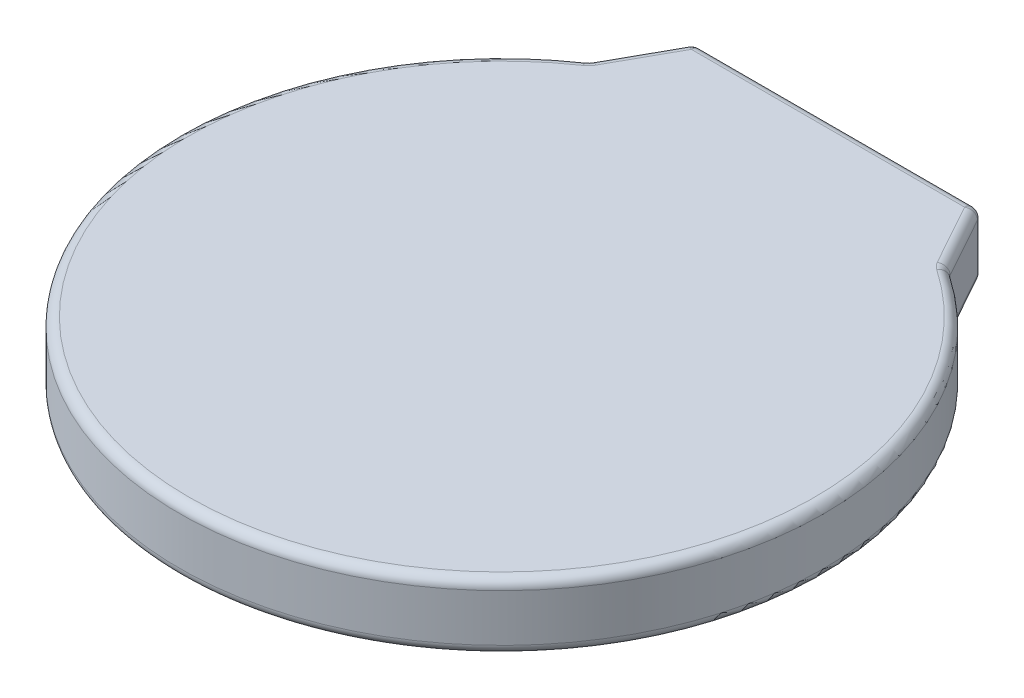
SolidWorks part; units mm, degrees
material "Zinc AC41A Alloy, As Cast"
ref_plane "Front Plane" through (0, 0, 0) normal (0, 0, 1) x (1, 0, 0)
ref_plane "Top Plane" through (0, 0, 0) normal (0, 1, 0) x (1, 0, 0)
ref_plane "Right Plane" through (0, 0, 0) normal (1, 0, 0) x (0, 0, -1)
sketch "Sketch1" plane through (0, 0, 0) normal (0, 1, 0) x (1, 0, 0)
  line L0 (0, -17) -> (0, 17) construction
  line L1 (0, 17) -> (0, 17.7) construction
  line L2 (-7.5, 17.7) -> (7.5, 17.7)
  line L3 (9.5, 14.0979) -> (-9.5, 14.0979) construction
  line L4 (7.5, 17.7) -> (9.5, 14.0979)
  line L5 (-7.5, 17.7) -> (-9.5, 14.0979)
  circle A0 centre (0, 0) radius 17
  point P9 (0, 17.7)
  dimension "D1" = 34
  dimension "D2" = 0.7
  dimension "D3" = 15
  dimension "D4" = 19
extrude "Boss-Extrude1" add sketch "Sketch1" along normal blind 3.5 contours A0 | A0 L4 L2 L5
fillet "Fillet1" radius 0.5 12 edges at (-8.5, 3.5, -15.8989) (-8.5, 0, -15.8989) (8.5, 3.5, -15.8989) (8.5, 0, -15.8989) (7.5, 1.75, -17.7) (0, 3.5, -17.7) (-7.5, 1.75, -17.7) (0, 0, -17.7) (-9.5, 1.75, -14.0979) (0, 3.5, 17) (9.5, 1.75, -14.0979) (0, 0, 17)
